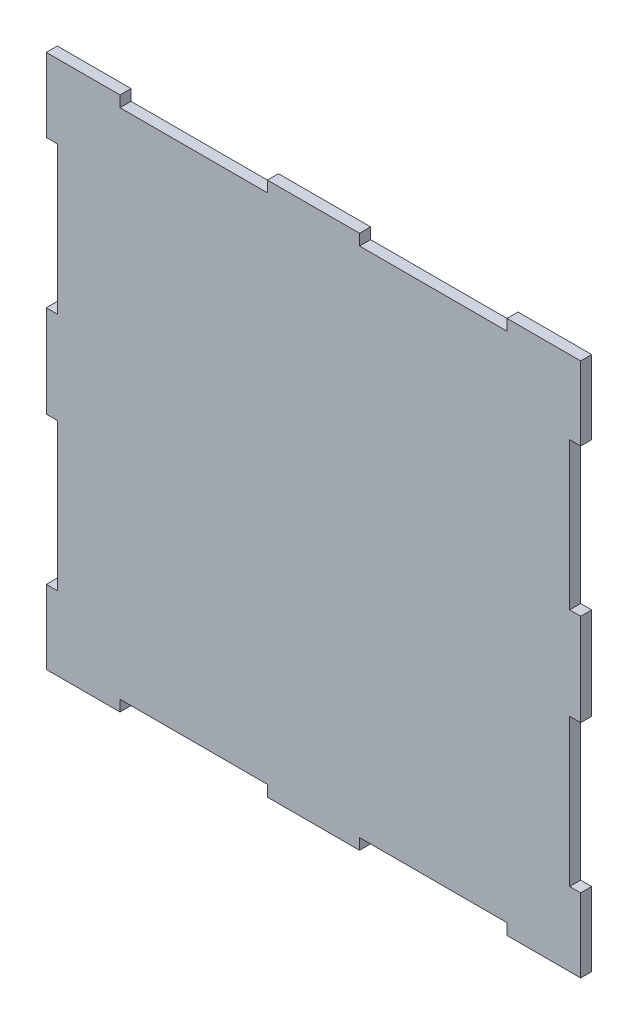
SolidWorks part; units mm, degrees
ref_plane "Front Plane" through (0, 0, 0) normal (0, 0, 1) x (1, 0, 0)
ref_plane "Top Plane" through (0, 0, 0) normal (0, 1, 0) x (1, 0, 0)
ref_plane "Right Plane" through (0, 0, 0) normal (1, 0, 0) x (0, 0, -1)
sketch "Sketch1" plane through (0, 0, 0) normal (0, 0, 1) x (1, 0, 0)
  line L1 (-72.5, 72.5) -> (72.5, 72.5)
  line L2 (-72.5, 72.5) -> (-72.5, -72.5)
  line L3 (-72.5, -72.5) -> (72.5, -72.5)
  line L4 (72.5, 72.5) -> (72.5, -72.5)
  line L5 (-72.5, 72.5) -> (72.5, -72.5) construction
  line L6 (-72.5, -72.5) -> (72.5, 72.5) construction
  point P0 (0, 0)
  dimension "D1" = 145
  dimension "D2" = 145
extrude "Boss-Extrude179" add sketch "Sketch1" along normal blind 3
sketch "Sketch2" plane through (0, 0, 3) normal (0, 0, 1) x (1, 0, 0)
  line L0 (-72.5, 0) -> (0, 0) construction
  line L1 (-72.5, 72.5) -> (-72.5, -72.5) construction
  line L2 (0, 0) -> (0, 72.5) construction
  line L3 (72.5, 72.5) -> (-72.5, 72.5) construction
  line L4 (-92.5, 52.5) -> (-92.5, -52.5) construction
  line L5 (-52.5, 72.5) -> (-12.5, 72.5)
  line L6 (-52.5, 72.5) -> (-52.5, 69.5)
  line L7 (-52.5, 69.5) -> (-12.5, 69.5)
  line L8 (-12.5, 72.5) -> (-12.5, 69.5)
  line L9 (12.5, 72.5) -> (52.5, 72.5)
  line L10 (12.5, 72.5) -> (12.5, 69.5)
  line L11 (12.5, 69.5) -> (52.5, 69.5)
  line L12 (52.5, 72.5) -> (52.5, 69.5)
  line L13 (-72.5, 52.5) -> (-69.5, 52.5)
  line L14 (-72.5, 52.5) -> (-72.5, 12.5)
  line L15 (-72.5, 12.5) -> (-69.5, 12.5)
  line L16 (-69.5, 52.5) -> (-69.5, 12.5)
  line L17 (-72.5, -12.5) -> (-69.5, -12.5)
  line L18 (-72.5, -12.5) -> (-72.5, -52.5)
  line L19 (-72.5, -52.5) -> (-69.5, -52.5)
  line L20 (-69.5, -12.5) -> (-69.5, -52.5)
  line L21 (-52.5, 92.5) -> (52.5, 92.5) construction
  line L22 (72.5, -72.5) -> (72.5, 72.5) construction
  line L23 (52.5, -72.5) -> (52.5, -69.5)
  line L24 (12.5, -69.5) -> (52.5, -69.5)
  line L25 (12.5, -72.5) -> (12.5, -69.5)
  line L26 (12.5, -72.5) -> (52.5, -72.5)
  line L27 (-12.5, -72.5) -> (-12.5, -69.5)
  line L28 (-52.5, -69.5) -> (-12.5, -69.5)
  line L29 (-52.5, -72.5) -> (-52.5, -69.5)
  line L30 (-52.5, -72.5) -> (-12.5, -72.5)
  line L31 (69.5, -12.5) -> (69.5, -52.5)
  line L32 (72.5, -52.5) -> (69.5, -52.5)
  line L33 (72.5, -12.5) -> (72.5, -52.5)
  line L34 (72.5, -12.5) -> (69.5, -12.5)
  line L35 (69.5, 52.5) -> (69.5, 12.5)
  line L36 (72.5, 12.5) -> (69.5, 12.5)
  line L37 (72.5, 52.5) -> (72.5, 12.5)
  line L38 (72.5, 52.5) -> (69.5, 52.5)
  point P29 (0, 92.5)
  point P31 (-92.5, 0)
  point P37 (52.5, 71)
  dimension "D1" = 3
  dimension "D2" = 40
  dimension "D3" = 20
  dimension "D4" = 20
  dimension "D5" = 20
  dimension "D6" = 20
extrude "Cut-Extrude1" cut sketch "Sketch2" against normal blind 3
